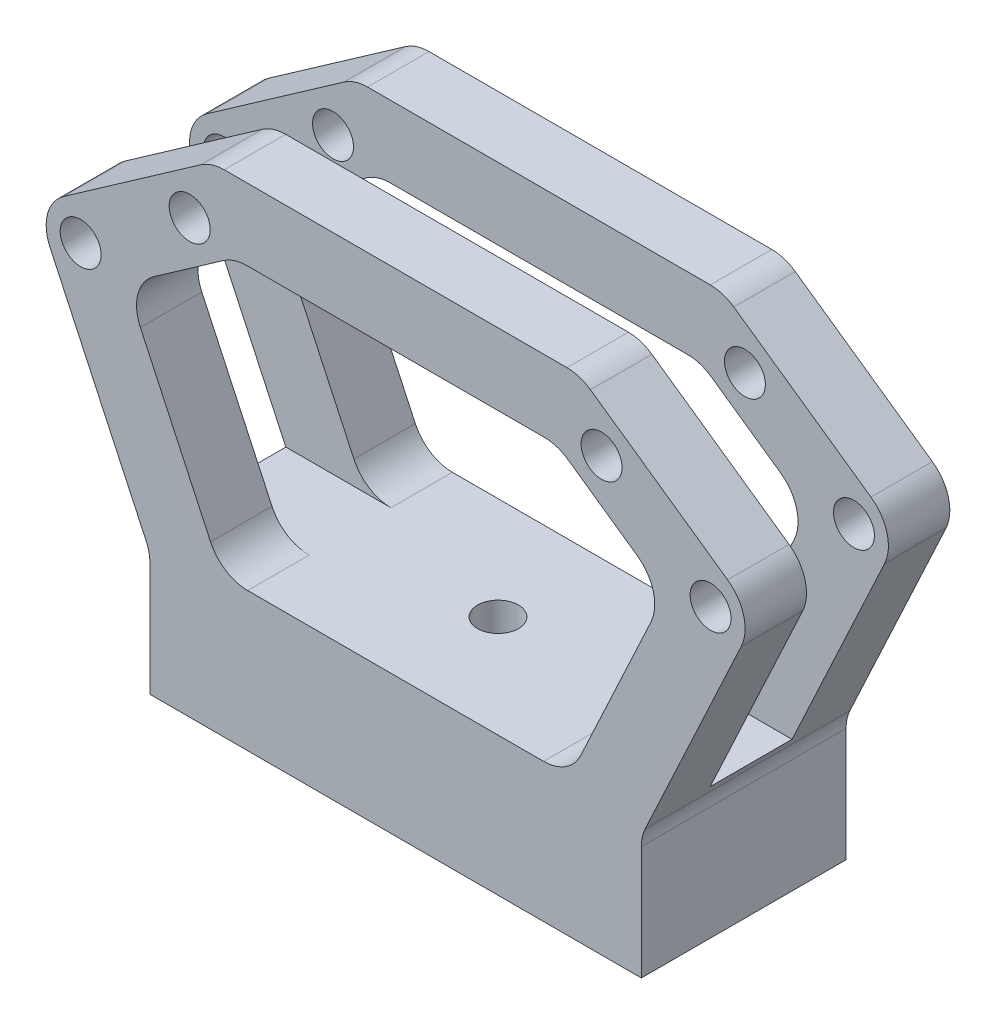
SolidWorks part; units mm, degrees
ref_plane "Front Plane" through (0, 0, 0) normal (0, 0, 1) x (1, 0, 0)
ref_plane "Top Plane" through (0, 0, 0) normal (0, 1, 0) x (1, 0, 0)
ref_plane "Right Plane" through (0, 0, 0) normal (1, 0, 0) x (0, 0, -1)
sketch "Sketch2" plane through (0, 0, 0) normal (0, 0, 1) x (1, 0, 0)
  line L0 (0, 0) -> (0, 120) construction
  line L1 (0, 120) -> (-45, 120)
  line L2 (-45, 120) -> (-87.9455, 89.9293)
  line L3 (-87.9455, 89.9293) -> (-60, 30)
  line L4 (-60, 30) -> (-60, 0)
  line L5 (-60, 0) -> (0, 0)
  line L6 (0, 102.5) -> (-39.4823, 102.5)
  line L7 (-39.4823, 102.5) -> (-65.8793, 84.0166)
  line L8 (-65.8793, 84.0166) -> (-42.5, 33.8797)
  line L9 (-42.5, 33.8797) -> (42.5, 33.8797)
  line L10 (0, 120) -> (45, 120)
  line L11 (-45.2711, 98.4466) -> (-55.3087, 112.7818) construction
  line L12 (-65.8793, 84.0166) -> (-87.9455, 89.9293) construction
  line L13 (-42.5, 33.8797) -> (-42.5, 17.5) construction
  line L14 (-42.5, 17.5) -> (0, 17.5) construction
  line L15 (0, 102.5) -> (39.4823, 102.5)
  line L16 (60, 0) -> (0, 0)
  line L17 (65.8793, 84.0166) -> (87.9455, 89.9293) construction
  line L18 (45.2711, 98.4466) -> (55.3087, 112.7818) construction
  line L19 (65.8793, 84.0166) -> (42.5, 33.8797)
  line L20 (39.4823, 102.5) -> (65.8793, 84.0166)
  line L21 (60, 30) -> (60, 0)
  line L22 (87.9455, 89.9293) -> (60, 30)
  line L23 (45, 120) -> (87.9455, 89.9293)
  circle A0 centre (-50.2899, 105.6142) radius 5
  circle A1 centre (-76.9124, 86.9729) radius 5
  circle A2 centre (76.9124, 86.9729) radius 5
  circle A3 centre (50.2899, 105.6142) radius 5
  point P17 (-76.9124, 86.9729)
  point P20 (-50.2899, 105.6142)
  point P25 (0, 33.8797)
  dimension "D8" = 10
  dimension "D9" = 10
  dimension "D1" = 45
  dimension "D2" = 60
  dimension "D3" = 120
  dimension "D4" = 100
  dimension "D5" = 25
  dimension "D6" = 30
  dimension "D10" = 32.5
  dimension "D7" = 17.5
extrude "Boss-Extrude2" add sketch "Sketch2" along normal blind 50
fillet "Fillet1" radius 10 12 edges at (-60, 30, 25) (-87.9455, 89.9293, 25) (-42.5, 33.8797, 25) (-65.8793, 84.0166, 25) (-39.4823, 102.5, 25) (39.4823, 102.5, 25) (65.8793, 84.0166, 25) (42.5, 33.8797, 25) (60, 30, 25) (87.9455, 89.9293, 25) (45, 120, 25) (-45, 120, 25)
sketch "Sketch3" plane through (-60, 0, 0) normal (-1, 0, 0) x (0, 0, 1)
  line L0 (15, 33.8797) -> (35, 33.8797)
  line L1 (35, 33.8797) -> (35, 120)
  line L2 (35, 120) -> (15, 120)
  line L3 (15, 120) -> (15, 33.8797)
  line L4 (0, 120) -> (50, 120) construction
  line L6 (0, 33.8797) -> (50, 33.8797) construction
  line L7 (0, 82.3244) -> (0, 32.0092) construction
  dimension "D1" = 15
  dimension "D2" = 20
extrude "Cut-Extrude1" cut sketch "Sketch3" against normal through all and the other way through all
sketch "Sketch4" plane through (0, 0, 0) normal (0, -1, 0) x (1, 0, 0)
  line L0 (-60, 50) -> (60, 50) construction
  circle A0 centre (0, 25) radius 5
  dimension "D2" = 10
  dimension "D1" = 25
extrude "Cut-Extrude2" cut sketch "Sketch4" against normal through all
